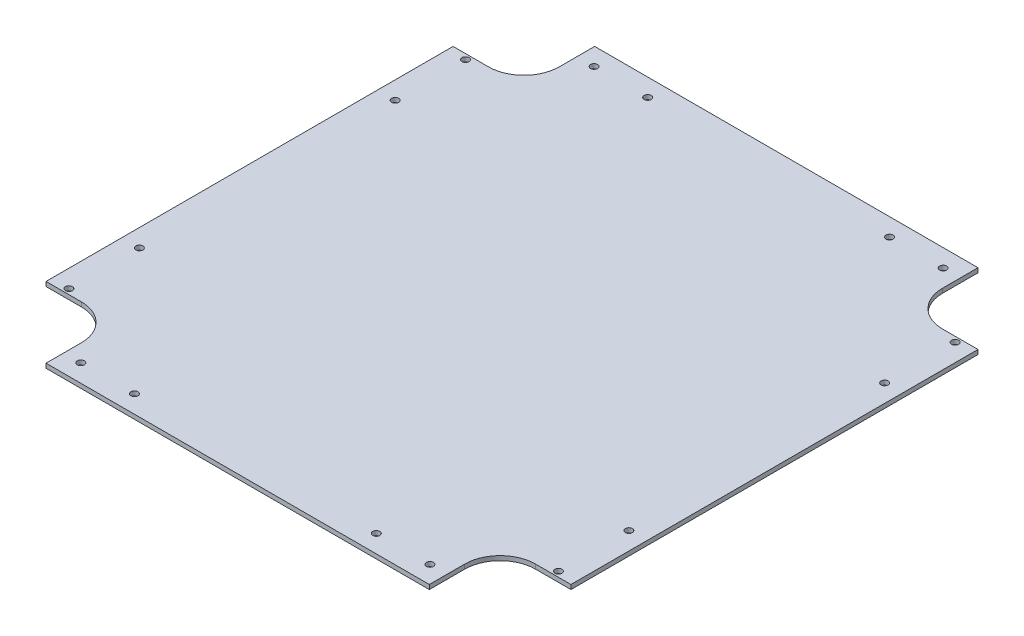
SolidWorks part; units mm, degrees
ref_plane "Front Plane" through (0, 0, 0) normal (0, 0, 1) x (1, 0, 0)
ref_plane "Top Plane" through (0, 0, 0) normal (0, 1, 0) x (1, 0, 0)
ref_plane "Right Plane" through (0, 0, 0) normal (1, 0, 0) x (0, 0, -1)
ref_plane "Plane1" through (0, -112.701, 0) normal (0, 1, 0) x (1, 0, 0)
sketch "Sketch2" plane through (0, -112.701, 0) normal (0, 1, 0) x (1, 0, 0)
  line L1 (-188.5638, 274.7375) -> (244.5958, 274.7375)
  line L2 (-188.5638, 274.7375) -> (-188.5638, 194.7375)
  line L3 (-188.5638, -345.2625) -> (244.5958, -345.2625)
  line L4 (244.5958, 274.7375) -> (244.5958, 194.7375)
  line L7 (-268.5638, 194.7375) -> (-188.5638, 194.7375)
  line L8 (-268.5638, 194.7375) -> (-268.5638, -265.2625)
  line L9 (-268.5638, -265.2625) -> (-188.5638, -265.2625)
  line L10 (324.5958, 194.7375) -> (324.5958, -265.2625)
  line L11 (-268.5638, -35.2625) -> (324.5958, -35.2625) construction
  line L13 (-188.5638, -265.2625) -> (-188.5638, -345.2625)
  line L14 (244.5958, 194.7375) -> (324.5958, 194.7375)
  line L15 (244.5958, -265.2625) -> (244.5958, -345.2625)
  line L16 (244.5958, -265.2625) -> (324.5958, -265.2625)
  line L17 (28.016, 274.7375) -> (28.016, -345.2625) construction
  line L20 (-20.7168, 274.7375) -> (-228.5638, 274.7375) construction
  line L21 (324.5958, -345.2625) -> (28.1987, -345.2625) construction
  line L23 (-265.3938, 234.7375) -> (-254.1938, 234.7375) construction
  line L24 (-228.5638, 260.3675) -> (-228.5638, 271.5675) construction
  line L25 (-248.5638, 194.7375) -> (-248.5638, -265.2625) construction
  line L26 (-248.5638, -325.2625) -> (-248.5638, 254.7375) construction
  line L27 (-188.5638, 254.7375) -> (244.5958, 254.7375) construction
  line L28 (-248.5638, 254.7375) -> (391.4362, 254.7375) construction
  line L30 (-268.5638, -305.2625) -> (-268.5638, 234.7375) construction
  line L31 (324.5958, -305.2625) -> (324.5958, 234.7375) construction
  circle A0 centre (-169.2084, 254.7375) radius 4
  circle A1 centre (-108.626, 254.7375) radius 4
  circle A2 centre (-248.5638, 188.8377) radius 4
  circle A3 centre (-248.5638, 109.252) radius 4
  circle A4 centre (304.5958, 109.252) radius 4
  circle A5 centre (164.658, 254.7375) radius 4
  circle A6 centre (225.2404, 254.7375) radius 4
  circle A7 centre (304.5958, 188.8377) radius 4
  circle A8 centre (304.5958, -259.3627) radius 4
  circle A9 centre (225.2404, -325.2625) radius 4
  circle A10 centre (164.658, -325.2625) radius 4
  circle A11 centre (304.5958, -179.777) radius 4
  circle A12 centre (-248.5638, -179.777) radius 4
  circle A13 centre (-248.5638, -259.3627) radius 4
  circle A14 centre (-108.626, -325.2625) radius 4
  circle A15 centre (-169.2084, -325.2625) radius 4
  point P13 (-340, 230)
  point P17 (28.016, -35.2625)
  point P18 (228.8233, 230)
  point P42 (-228.5638, 265.9675)
  point P70 (-108.626, 290)
  point P71 (-169.2084, 290)
  point P72 (-300, 230)
  point P73 (0, 0)
  point P75 (0, 0)
  point P76 (340, 230)
  point P77 (340, 230)
  dimension "D3" = 8
  dimension "D1" = 40
  dimension "D2" = 40
extrude "Boss-Extrude1" add sketch "Sketch2" along normal blind 5
fillet "Fillet1" radius 40 4 edges at (-188.5638, -110.201, -194.7375) (244.5958, -110.201, -194.7375) (244.5958, -110.201, 265.2625) (-188.5638, -110.201, 265.2625)
